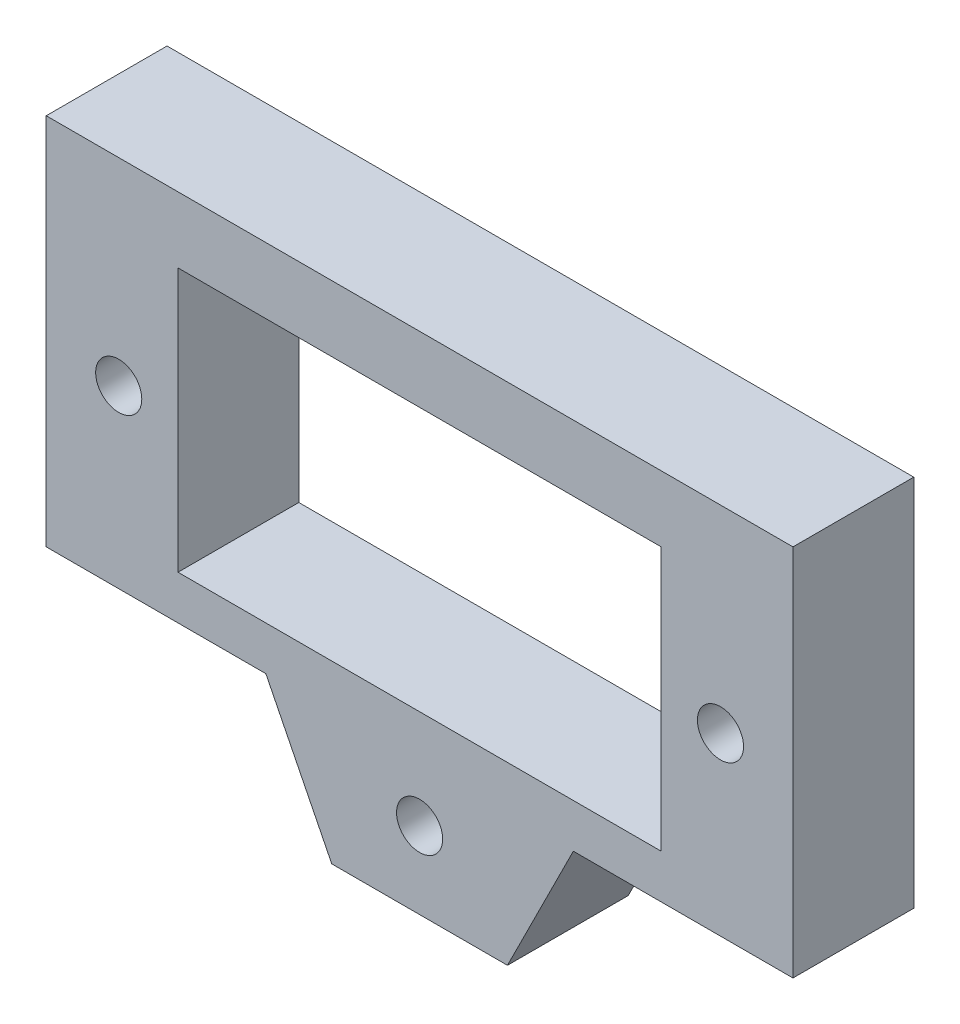
SolidWorks part; units mm, degrees
material "ﾁｰｸ材"
ref_plane "正面" through (0, 0, 0) normal (0, 0, 1) x (1, 0, 0)
ref_plane "平面" through (0, 0, 0) normal (0, 1, 0) x (1, 0, 0)
ref_plane "右側面" through (0, 0, 0) normal (1, 0, 0) x (0, 0, -1)
sketch "ｽｹｯﾁ1" plane through (0, 0, 0) normal (0, 0, 1) x (1, 0, 0)
  line L0 (-17, -8) -> (-7, -8)
  line L1 (11, 6) -> (-11, 6)
  line L2 (11, 6) -> (11, -6)
  line L3 (11, -6) -> (-11, -6)
  line L4 (-11, 6) -> (-11, -6)
  line L5 (11, 6) -> (-11, -6) construction
  line L6 (11, -6) -> (-11, 6) construction
  line L7 (-17, 9) -> (17, 9)
  line L8 (-17, 9) -> (-17, -8)
  line L10 (17, 9) -> (17, -8)
  line L11 (-7, -8) -> (-4, -14)
  line L12 (-4, -14) -> (4, -14)
  line L13 (4, -14) -> (7, -8)
  line L14 (7, -8) -> (17, -8)
  circle A0 centre (-13.7, 0) radius 1.05
  circle A1 centre (13.7, 0) radius 1.05
  circle A2 centre (0, -10.5) radius 1.05
  point P0 (0, 0)
  dimension "D3" = 2.1
  dimension "D4" = 2.1
  dimension "D15" = 2.1
  dimension "D1" = 22
  dimension "D2" = 12
  dimension "D5" = 2.7
  dimension "D6" = 2.7
  dimension "D7" = 9
  dimension "D8" = 17
  dimension "D9" = 17
  dimension "D10" = 10
  dimension "D11" = 6
  dimension "D12" = 13
  dimension "D13" = 14
  dimension "D14" = 8
  dimension "D16" = 10.5
extrude "ﾎﾞｽ - 押し出し1" add sketch "ｽｹｯﾁ1" along normal blind 5.5
